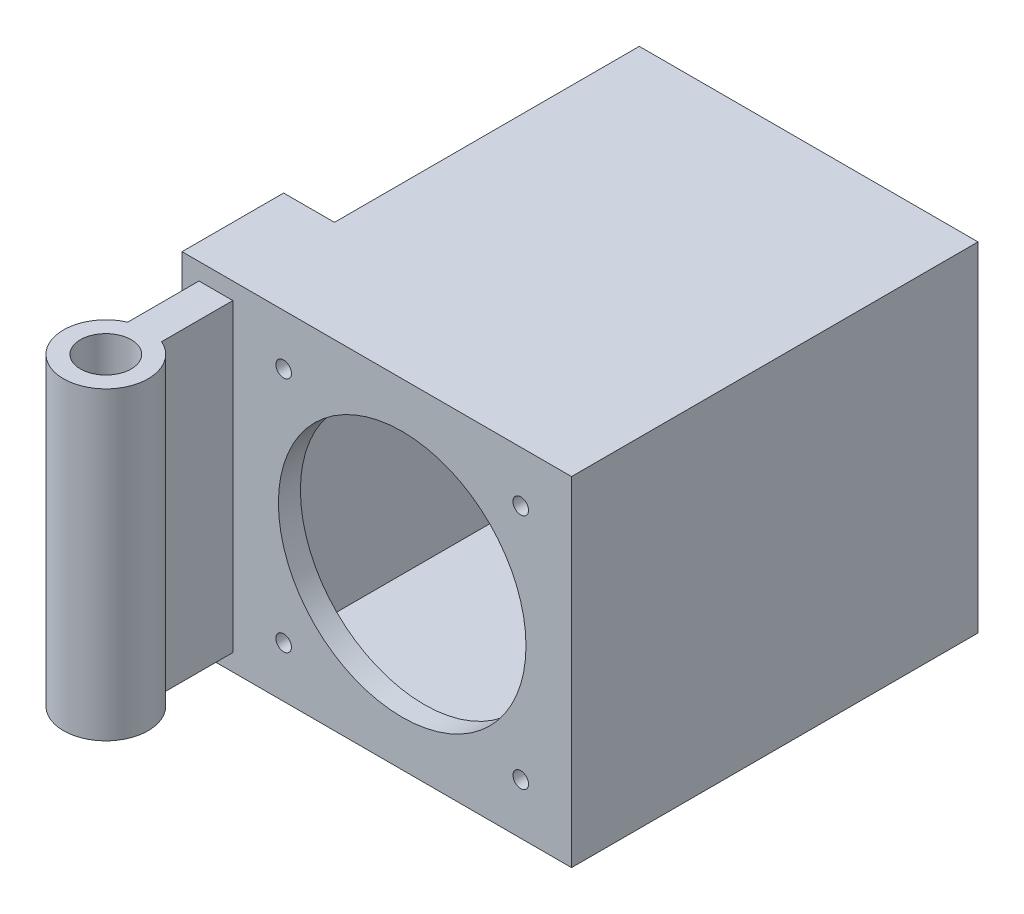
SolidWorks part; units mm, degrees
ref_plane "Front Plane" through (0, 0, 0) normal (0, 0, 1) x (1, 0, 0)
ref_plane "Top Plane" through (0, 0, 0) normal (0, 1, 0) x (1, 0, 0)
ref_plane "Right Plane" through (0, 0, 0) normal (1, 0, 0) x (0, 0, -1)
sketch "Sketch1" plane through (0, 0, 0) normal (0, 0, 1) x (1, 0, 0)
  line L1 (-50, -50) -> (50, -50)
  line L2 (-50, -50) -> (-50, 50)
  line L3 (-50, 50) -> (50, 50)
  line L4 (50, -50) -> (50, 50)
  line L5 (-50, -50) -> (50, 50) construction
  line L6 (-50, 50) -> (50, -50) construction
  point P0 (0, 0)
  dimension "D1" = 100
  dimension "D2" = 100
extrude "Boss-Extrude1" add sketch "Sketch1" along normal mid plane 120 contours L3 L4 L1 L2
sketch "Sketch2" plane through (0, 0, -60) normal (0, 0, -1) x (-1, 0, 0)
  line L1 (-43.5, -43.5) -> (43.5, -43.5)
  line L2 (-43.5, -43.5) -> (-43.5, 43.5)
  line L3 (-43.5, 43.5) -> (43.5, 43.5)
  line L4 (43.5, -43.5) -> (43.5, 43.5)
  line L5 (-43.5, -43.5) -> (43.5, 43.5) construction
  line L6 (-43.5, 43.5) -> (43.5, -43.5) construction
  point P0 (0, 0)
  dimension "D1" = 87
  dimension "D2" = 87
extrude "Cut-Extrude1" cut sketch "Sketch2" against normal offset from surface (113.5 mm away) 6.5 up to face at (0, 0, 60)
sketch "Sketch4" plane through (0, 0, 60) normal (0, 0, 1) x (1, 0, 0)
  circle A0 centre (0, 0) radius 36.55
  dimension "D1" = 73.1
extrude "Cut-Extrude2" cut sketch "Sketch4" against normal up to surface (6.5 mm away) up to face at (0, 0, 53.5)
hole_wizard "Ø4.6 (4.6) Diameter Hole1" positions "Sketch5" profile "Sketch6" hole size "Ø4.6" standard "ANSI Metric"
sketch "Sketch5" plane through (0, 0, 60) normal (0, 0, 1) x (1, 0, 0)
  point P0 (-35, 35)
  dimension "D1" = 35
  dimension "D2" = 35
sketch "Sketch6" plane through (-35, 35, 60) normal (1, 0, 0) x (0, -1, 0)
  line L0 (0, 0) -> (0, 7.881)
  line L1 (0, 7.881) -> (2.3, 6.499)
  line L2 (2.3, 6.499) -> (2.3, 0)
  line L5 (2.3, 0) -> (0, 0)
  line L10 (0, 7.881) -> (-2.3, 6.499) construction
  line L11 (0, -6.35) -> (0, 107.95) construction
  dimension "Hole Dia." = 4.6
  dimension "Hole Depth" = 6.499
  dimension "Drill Angle" = 118
pattern_circular "CirPattern1" count 4 over 360 about axis through (0, 0, 0) along (0, 0, 1) of "Ø4.6 (4.6) Diameter Hole1"
sketch "Sketch13" plane through (-50, 0, 0) normal (-1, 0, 0) x (0, 0, 1)
  line L0 (60, 50) -> (-60, 50) construction
  line L1 (30, -50) -> (60, -50)
  line L2 (30, -50) -> (30, 50)
  line L3 (30, 50) -> (60, 50)
  line L4 (60, -50) -> (60, 50)
  line L5 (30, -50) -> (60, 50) construction
  line L6 (30, 50) -> (60, -50) construction
  line L7 (60, -50) -> (60, 50) construction
  line L8 (60, -50) -> (-60, -50) construction
  point P0 (45, 0)
  dimension "D1" = 30
extrude "Boss-Extrude6" add sketch "Sketch13" along normal blind 15
sketch "Sketch14" plane through (0, 0, 60) normal (0, 0, 1) x (1, 0, 0)
  line L0 (-65, 50) -> (50, 50) construction
  line L1 (-60, -45) -> (-50, -45)
  line L2 (-60, -45) -> (-60, 45)
  line L3 (-60, 45) -> (-50, 45)
  line L4 (-50, -45) -> (-50, 45)
  line L5 (-60, -45) -> (-50, 45) construction
  line L6 (-60, 45) -> (-50, -45) construction
  line L8 (-65, -50) -> (-65, 50) construction
  point P0 (-55, 0)
  dimension "D1" = 5
  dimension "D2" = 10
  dimension "D3" = 5
sketch "Sketch15" plane through (0, 0, 0) normal (0, 1, 0) x (1, 0, 0)
  line L0 (-65, -60) -> (50, -60) construction
  circle A0 centre (-55, -92.5) radius 12.5
  dimension "D2" = 25
  dimension "D1" = 32.5
extrude "Boss-Extrude7" add sketch "Sketch15" along normal offset from surface 5 and the other way offset from surface (45 mm away) 5 separate body up to face at (-21.6667, 50, 10) other way up to face at (-21.6667, -50, 10)
extrude "Boss-Extrude8" add sketch "Sketch14" along normal up to surface (21.0436 mm away)
sketch "Sketch16" plane through (0, 45, 0) normal (0, 1, 0) x (1, 0, 0)
  circle A0 centre (-55, -92.5) radius 7.5
  arc A1 (-60, -81.0436) -> (-50, -81.0436) centre (-55, -92.5) ccw construction
  dimension "D1" = 15
extrude "Cut-Extrude4" cut sketch "Sketch16" against normal up to surface (90 mm away)
sketch "Sketch17" plane through (-65, 0, 0) normal (1, 0, 0) x (0, 0, -1)
  circle A0 centre (-92.5, 0) radius 2.25
  dimension "D1" = 4.5
  dimension "D2" = 7.5
extrude "Cut-Extrude5" cut sketch "Sketch17" against normal up to surface and the other way up to surface up to face at (-55, 0, 93.0218) other way up to face at (-55, -45, 100)
equation "\"D2@Sketch1\"=\"D1@Sketch1\""
equation "\"D2@Sketch2\"=\"D1@Sketch2\""
equation "\"D1@Sketch15\"=\"D2@Sketch15\"/2+20"
